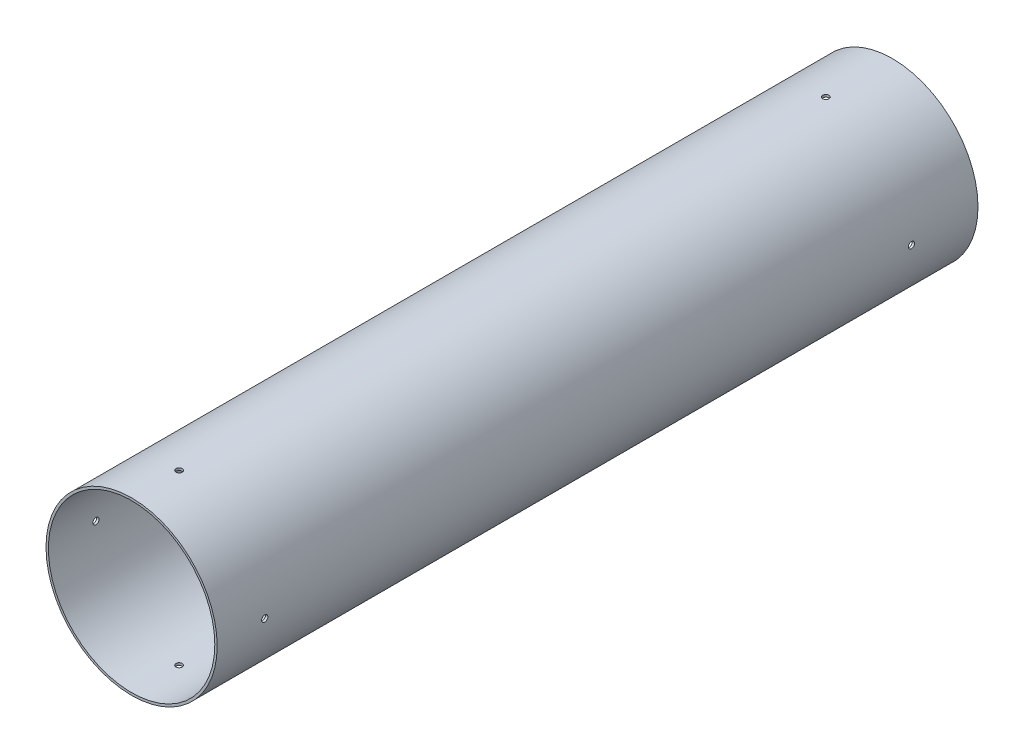
SolidWorks part; units mm, degrees
ref_plane "Front Plane" through (0, 0, 0) normal (0, 0, 1) x (1, 0, 0)
ref_plane "Top Plane" through (0, 0, 0) normal (0, 1, 0) x (1, 0, 0)
ref_plane "Right Plane" through (0, 0, 0) normal (1, 0, 0) x (0, 0, -1)
sketch "Sketch1" plane through (0, 0, 0) normal (0, 0, 1) x (1, 0, 0)
  circle A0 centre (0, 0) radius 45
  circle A1 centre (0, 0) radius 43.75
  dimension "D1" = 90
  dimension "D2" = 87.5
extrude "Boss-Extrude1" add sketch "Sketch1" along normal blind 400
sketch "Sketch2" plane through (0, 0, 0) normal (1, 0, 0) x (0, 0, -1)
  line L0 (0, 0) -> (-35, 0) construction
  line L1 (-400, 0) -> (-375, 0) construction
  line L2 (-400, 45) -> (-400, -45) construction
  circle A0 centre (-35, 0) radius 1.65
  circle A1 centre (-375, 0) radius 1.65
  dimension "D2" = 3.3
  dimension "D1" = 35
  dimension "D3" = 25
extrude "Cut-Extrude1" cut sketch "Sketch2" against normal through all
pattern_circular "CirPattern1" count 4 over 360 about axis through (0, 0, 400) along (0, 0, -1) of "Cut-Extrude1"
